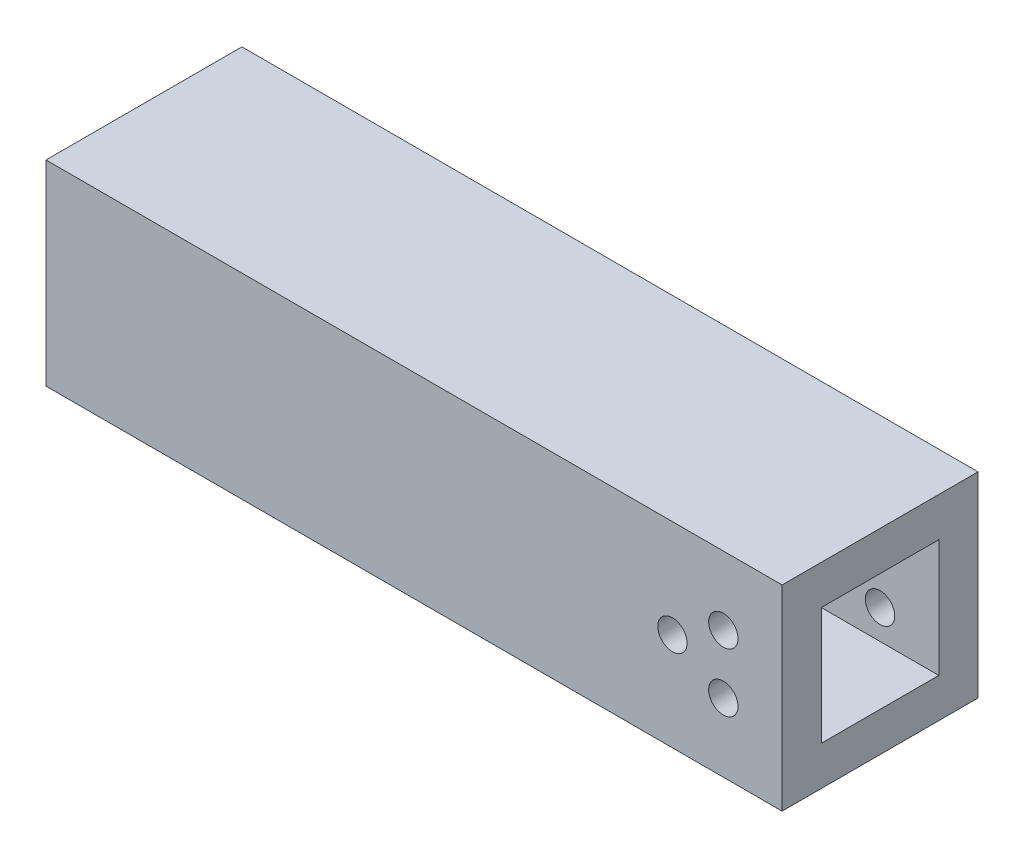
SolidWorks part; units mm, degrees
ref_plane "Front Plane" through (0, 0, 0) normal (1, 0, 0) x (0, 1, 0)
ref_plane "Top Plane" through (0, 0, 0) normal (0, 0, 1) x (0, 1, 0)
ref_plane "Right Plane" through (0, 0, 0) normal (0, 1, 0) x (-1, 0, 0)
sketch "Sketch1" plane through (0, 0, 0) normal (1, 0, 0) x (0, 1, 0)
  line L0 (-31.75, 31.75) -> (31.75, 31.75)
  line L1 (-31.75, 31.75) -> (-31.75, -31.75)
  line L2 (-31.75, -31.75) -> (31.75, -31.75)
  line L3 (31.75, 31.75) -> (31.75, -31.75)
  line L4 (-19.05, 19.05) -> (19.05, 19.05)
  line L5 (-19.05, 19.05) -> (-19.05, -19.05)
  line L6 (-19.05, -19.05) -> (19.05, -19.05)
  line L7 (19.05, 19.05) -> (19.05, -19.05)
  dimension "D1" = 38.1
  dimension "D2" = 38.1
  dimension "D3" = 12.7
  dimension "D4" = 12.7
  dimension "D5" = 63.5
  dimension "D6" = 63.5
extrude "Boss-Extrude1" add sketch "Sketch1" along normal blind 50.8
sketch "Sketch5" plane through (0, 0, 0) normal (-1, 0, 0) x (0, 0, 1)
  line L0 (-31.75, 31.75) -> (31.75, 31.75) construction
  line L1 (-31.75, 31.75) -> (31.75, 31.75)
  line L2 (-31.75, 31.75) -> (-31.75, -31.75)
  line L3 (-31.75, -31.75) -> (31.75, -31.75)
  line L4 (31.75, 31.75) -> (31.75, -31.75)
  line L5 (-31.75, -31.75) -> (-31.75, 31.75) construction
  line L6 (31.75, 31.75) -> (31.75, -31.75) construction
  line L7 (31.75, -31.75) -> (-31.75, -31.75) construction
  circle A0 centre (0, 0) radius 26.9875
  dimension "D5" = 53.975
  dimension "D1" = 0
  dimension "D2" = 0
  dimension "D3" = 0
  dimension "D4" = 0
  dimension "D6" = 31.75
  dimension "D7" = 31.75
extrude "Boss-Extrude2" add sketch "Sketch5" along normal blind 187.8
sketch "Sketch15" plane through (0, 0, -31.75) normal (0, 0, -1) x (-1, 0, 0)
  line L0 (-50.8, -31.75) -> (-50.8, 31.75) construction
  line L1 (-50.8, -31.75) -> (187.8, -31.75) construction
  circle A0 centre (-41.0402, -0.3093) radius 13.4147
  point P2 (-31.75, 9.525)
  point P4 (-31.75, -9.525)
  point P6 (-15.2522, 0)
  dimension "D1" = 19.05
  dimension "D2" = 19.05
  dimension "D3" = 19.05
  dimension "D4" = 19.05
  dimension "D5" = 19.05
  dimension "D6" = 31.75
hole_wizard "#97 (0.375) Diameter Hole2" positions "Sketch15" profile "Sketch16" hole size "#97" standard "ANSI Inch"
sketch "Sketch16" plane through (15.2522, 0, -31.75) normal (1, 0, 0) x (0, 1, 0)
  line L0 (0, 0) -> (0, 12.7)
  line L1 (0, 12.7) -> (4.7625, 12.7)
  line L2 (4.7625, 12.7) -> (4.7625, 0)
  line L5 (4.7625, 0) -> (0, 0)
  line L10 (0, 12.7) -> (-4.7625, 12.7) construction
  line L11 (0, -6.35) -> (0, 107.95) construction
  dimension "Hole Dia." = 9.525
  dimension "Hole Depth" = 12.7
  dimension "Drill Angle" = 180
sketch "Sketch17" plane through (0, 0, 31.75) normal (0, 0, 1) x (1, 0, 0)
  line L0 (50.8, 31.75) -> (50.8, -31.75) construction
  line L1 (50.8, 31.75) -> (-187.8, 31.75) construction
  circle A0 centre (16.237, 1.9972) radius 10.6033
  point P3 (31.75, 9.525)
  point P5 (15.2522, 0)
  point P7 (31.75, -9.525)
  dimension "D1" = 19.05
  dimension "D2" = 19.05
  dimension "D3" = 19.05
  dimension ".75in" = 19.05
  dimension "D4" = 19.05
  dimension "D5" = 31.75
hole_wizard "#97 (0.375) Diameter Hole3" positions "Sketch17" profile "Sketch18" hole size "#97" standard "ANSI Inch"
sketch "Sketch18" plane through (31.75, -9.525, 31.75) normal (1, 0, 0) x (0, -1, 0)
  line L0 (0, 0) -> (0, 12.7)
  line L1 (0, 12.7) -> (4.7625, 12.7)
  line L2 (4.7625, 12.7) -> (4.7625, 0)
  line L5 (4.7625, 0) -> (0, 0)
  line L10 (0, 12.7) -> (-4.7625, 12.7) construction
  line L11 (0, -6.35) -> (0, 107.95) construction
  dimension "Hole Dia." = 9.525
  dimension "Hole Depth" = 12.7
  dimension "Drill Angle" = 180
